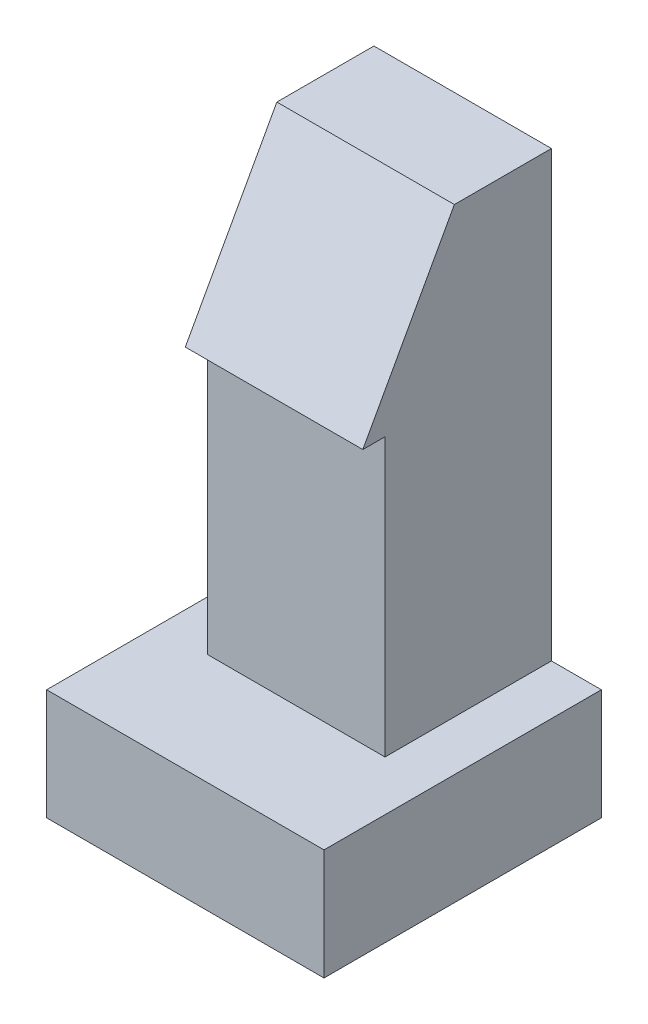
SolidWorks part; units mm, degrees
ref_plane "Front Plane" through (0, 0, 0) normal (0, 0, 1) x (1, 0, 0)
ref_plane "Top Plane" through (0, 0, 0) normal (0, 1, 0) x (1, 0, 0)
ref_plane "Right Plane" through (0, 0, 0) normal (1, 0, 0) x (0, 0, -1)
sketch "Sketch1" plane through (0, 0, 0) normal (0, 1, 0) x (1, 0, 0)
  line L1 (-2.5, 2.5) -> (2.5, 2.5)
  line L2 (-2.5, 2.5) -> (-2.5, -2.5)
  line L3 (-2.5, -2.5) -> (2.5, -2.5)
  line L4 (2.5, 2.5) -> (2.5, -2.5)
  line L5 (-2.5, 2.5) -> (2.5, -2.5) construction
  line L6 (-2.5, -2.5) -> (2.5, 2.5) construction
  point P0 (0, 0)
  dimension "D1" = 5
extrude "Boss-Extrude1" add sketch "Sketch1" along normal blind 2
sketch "Sketch2" plane through (0, 2, 0) normal (0, 1, 0) x (1, 0, 0)
  line L0 (2.5, 2.5) -> (-2.5, 2.5) construction
  line L1 (-1.6, 2.5) -> (1.6, 2.5)
  line L2 (-1.6, 2.5) -> (-1.6, -0.5)
  line L3 (-1.6, -0.5) -> (1.6, -0.5)
  line L4 (1.6, 2.5) -> (1.6, -0.5)
  point P6 (0, 2.5)
  dimension "D1" = 3.2
  dimension "D2" = 3
extrude "Boss-Extrude2" add sketch "Sketch2" along normal blind 5
sketch "Sketch3" plane through (0, 7, 0) normal (0, 1, 0) x (1, 0, 0)
  line L0 (1.6, -0.5) -> (1.6, 2.5) construction
  line L1 (-1.6, 2.5) -> (1.6, 2.5)
  line L2 (-1.6, 2.5) -> (-1.6, -0.9)
  line L3 (-1.6, -0.9) -> (1.6, -0.9)
  line L4 (1.6, 2.5) -> (1.6, -0.9)
  dimension "D1" = 3.4
extrude "Boss-Extrude3" add sketch "Sketch3" along normal blind 3
sketch "Sketch4" plane through (1.6, 0, 0) normal (1, 0, 0) x (0, 0, -1)
  line L0 (-0.9, 7) -> (0.75, 10)
  line L1 (0.75, 10) -> (-0.9, 10)
  line L2 (-0.9, 10) -> (-0.9, 7)
  point P4 (0.8217, 10)
  dimension "D1" = 1.75
extrude "Cut-Extrude1" cut sketch "Sketch4" against normal through all
